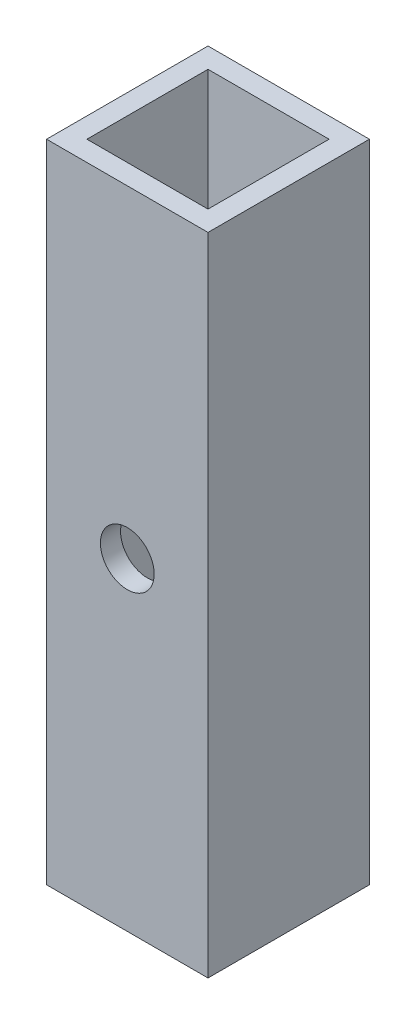
SolidWorks part; units mm, degrees
material "6061-T6 (SS)"
ref_plane "Front Plane" through (0, 0, 0) normal (0, 0, 1) x (1, 0, 0)
ref_plane "Top Plane" through (0, 0, 0) normal (0, 1, 0) x (1, 0, 0)
ref_plane "Right Plane" through (0, 0, 0) normal (1, 0, 0) x (0, 0, -1)
sketch "Sketch1" plane through (0, 0, 0) normal (0, 1, 0) x (1, 0, 0)
  line L0 (0, 19.05) -> (4.7625, 19.05) construction
  line L1 (0, 0) -> (38.1, 0)
  line L2 (0, 0) -> (0, 38.1)
  line L3 (0, 38.1) -> (38.1, 38.1)
  line L4 (38.1, 0) -> (38.1, 38.1)
  line L5 (4.7625, 4.7625) -> (33.3375, 4.7625)
  line L6 (4.7625, 4.7625) -> (4.7625, 33.3375)
  line L7 (4.7625, 33.3375) -> (33.3375, 33.3375)
  line L8 (33.3375, 4.7625) -> (33.3375, 33.3375)
  line L9 (33.3375, 19.05) -> (38.1, 19.05) construction
  line L10 (19.05, 4.7625) -> (19.05, 0) construction
  line L11 (19.05, 33.3375) -> (19.05, 38.1) construction
  dimension "D1" = 38.1
  dimension "D2" = 38.1
  dimension "D3" = 4.7625
extrude "Boss-Extrude1" add sketch "Sketch1" along normal blind 152.4
hole_wizard "1/2 (0.5) Diameter Hole1" positions "Sketch3" profile "Sketch2" hole size "1/2" standard "ANSI Inch" end condition through all
sketch "Sketch3" plane through (0, 0, 0) normal (0, 0, 1) x (1, 0, 0)
  line L0 (19.05, 0) -> (19.05, 76.2) construction
  line L1 (0, 0) -> (38.1, 0) construction
  line L2 (19.05, 76.2) -> (19.05, 152.4) construction
  line L3 (0, 152.4) -> (38.1, 152.4) construction
  point P0 (19.05, 76.2)
sketch "Sketch2" plane through (19.05, 76.2, 0) normal (1, 0, 0) x (0, -1, 0)
  line L0 (0, 0) -> (0, 38.1)
  line L1 (0, 38.1) -> (6.35, 38.1)
  line L2 (6.35, 38.1) -> (6.35, 0)
  line L5 (6.35, 0) -> (0, 0)
  line L11 (0, -6.35) -> (0, 107.95) construction
  dimension "Thru Hole Dia." = 12.7
  dimension "Thru Hole Depth" = 38.1
